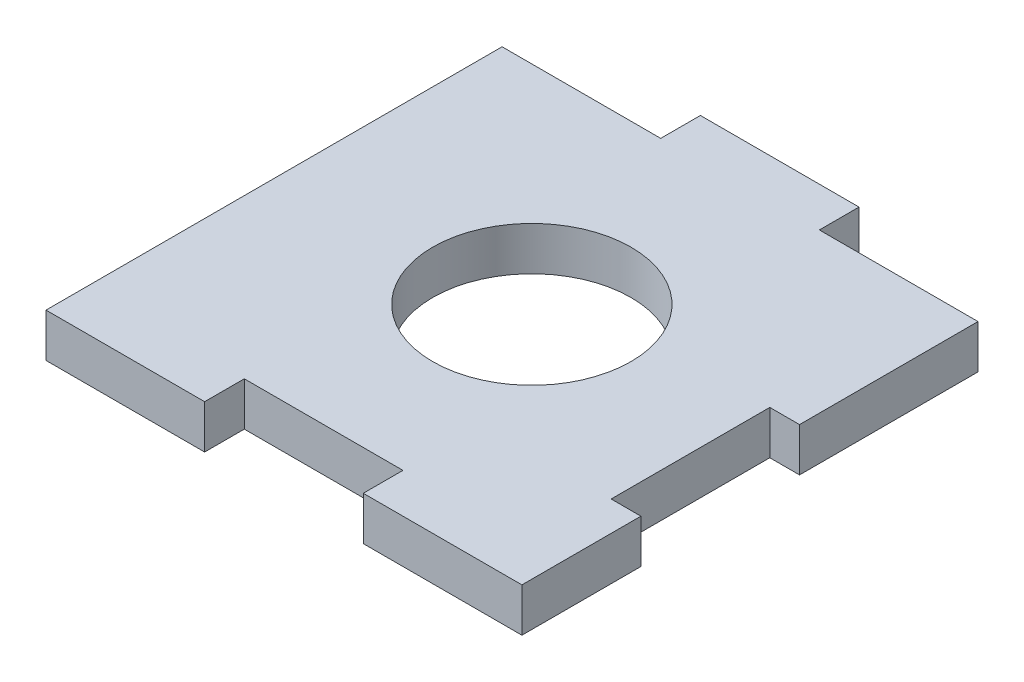
SolidWorks part; units mm, degrees
material "cardboard"
ref_plane "Front Plane" through (0, 0, 0) normal (0, 0, 1) x (1, 0, 0)
ref_plane "Top Plane" through (0, 0, 0) normal (0, 1, 0) x (1, 0, 0)
ref_plane "Right Plane" through (0, 0, 0) normal (1, 0, 0) x (0, 0, -1)
sketch "Sketch1" plane through (0, 0, 0) normal (0, 1, 0) x (1, 0, 0)
  line L0 (78.5546, 12.4023) -> (71.7044, 8.4474)
  line L1 (104.0546, -11.5977) -> (110.9047, -7.6428)
  line L2 (119.2044, 8.4474) -> (110.9047, 8.4474)
  line L3 (119.2044, -7.6428) -> (110.9047, -7.6428)
  line L4 (71.7044, 8.4474) -> (63.4047, 8.4474)
  line L5 (126.0546, 12.4023) -> (119.2044, 8.4474)
  line L6 (126.0546, -11.5977) -> (119.2044, -7.6428)
  line L7 (104.0546, 12.4023) -> (110.9047, 8.4474)
  line L8 (126.0546, 12.4023) -> (138.8046, 12.4023)
  line L9 (126.0546, -11.5977) -> (162.8046, -11.5977)
  line L10 (56.5546, 12.4023) -> (63.4047, 8.4474)
  line L11 (56.5546, -11.5977) -> (63.4047, -7.6428)
  line L12 (78.5546, -11.5977) -> (71.7044, -7.6428)
  line L13 (71.7044, -7.6428) -> (63.4047, -7.6428)
  line L14 (78.5546, 12.4023) -> (104.0546, 12.4023)
  line L15 (78.5546, -11.5977) -> (104.0546, -11.5977)
  line L16 (-11.1954, 78.1523) -> (-7.2405, 71.3021)
  line L17 (12.8046, 103.6523) -> (8.8496, 110.5024)
  line L18 (-7.2405, 118.8021) -> (-7.2405, 110.5024)
  line L19 (8.8496, 118.8021) -> (8.8496, 110.5024)
  line L20 (-7.2405, 71.3021) -> (-7.2405, 63.0024)
  line L21 (-11.1954, 125.6523) -> (-7.2405, 118.8021)
  line L22 (12.8046, 125.6523) -> (8.8496, 118.8021)
  line L23 (-11.1954, 103.6523) -> (-7.2405, 110.5024)
  line L24 (-11.1954, 125.6523) -> (-11.1954, 138.4023)
  line L25 (12.8046, 125.6523) -> (12.8046, 162.4023)
  line L26 (-11.1954, 56.1523) -> (-7.2405, 63.0024)
  line L27 (12.8046, 56.1523) -> (8.8496, 63.0024)
  line L28 (12.8046, 78.1523) -> (8.8496, 71.3021)
  line L29 (8.8496, 71.3021) -> (8.8496, 63.0024)
  line L30 (-11.1954, 78.1523) -> (-11.1954, 103.6523)
  line L31 (12.8046, 78.1523) -> (12.8046, 103.6523)
  line L32 (91.3046, 37.4023) -> (91.3046, 17.4023)
  line L33 (90.3046, 37.4023) -> (90.3046, 31.4023)
  line L34 (37.8046, 12.4023) -> (43.8046, 12.4023)
  line L35 (90.3046, 31.4023) -> (92.3046, 31.4023)
  line L36 (42.5546, 12.4023) -> (42.5546, 10.4023)
  line L37 (43.8046, 12.4023) -> (56.5546, 12.4023)
  line L38 (138.8046, 12.4023) -> (138.8046, -11.5977)
  line L39 (138.8046, 12.4023) -> (162.8046, 12.4023)
  line L40 (162.8046, 12.4023) -> (162.8046, 10.4023)
  line L41 (-27.6918, 14.7566) -> (0.8046, -13.7398)
  line L42 (-27.6918, 14.7566) -> (-13.5497, 28.8987)
  line L43 (0.8046, -13.7398) -> (14.9467, 0.4023)
  line L44 (-13.5497, 28.8987) -> (14.9467, 0.4023)
  line L45 (138.8046, 12.4023) -> (138.8046, 37.4023)
  line L46 (40.8046, 37.4023) -> (162.8046, 37.4023)
  line L47 (162.8046, 37.4023) -> (162.8046, 12.4023)
  line L48 (92.3046, 31.4023) -> (92.3046, 23.4023)
  line L49 (138.8046, 37.4023) -> (138.8046, 61.4023)
  line L50 (138.8046, 61.4023) -> (147.8046, 61.4023)
  line L51 (43.8046, 37.4023) -> (43.8046, 17.4023)
  line L52 (162.8046, 61.4023) -> (162.8046, 51.7243)
  line L53 (147.8046, 61.4023) -> (147.8046, 63.6023)
  line L54 (153.8046, 63.6023) -> (153.8046, 61.4023)
  line L55 (153.8046, 61.4023) -> (162.8046, 61.4023)
  line L56 (-58.1954, 138.4023) -> (-58.1954, 113.9023)
  line L57 (-38.1954, 113.9023) -> (-38.1954, 138.4023)
  line L58 (92.3046, 23.4023) -> (90.3046, 23.4023)
  line L59 (138.8046, -11.5977) -> (138.8046, -36.5977)
  line L60 (147.8046, -36.5977) -> (153.8046, -36.5977)
  line L61 (162.8046, -36.5977) -> (162.8046, -11.5977)
  line L62 (43.8046, -36.5977) -> (43.8046, -16.5977)
  line L63 (138.8046, -36.5977) -> (138.8046, -37.7777)
  line L64 (153.8046, -37.7777) -> (162.8046, -37.7777)
  line L65 (162.8046, -37.7777) -> (162.8046, -36.5977)
  line L66 (147.8046, -37.7777) -> (147.8046, -36.5977)
  line L67 (153.8046, -37.7777) -> (153.8046, -36.5977)
  line L68 (-37.3754, -137.5977) -> (-37.3754, -146.5977)
  line L69 (90.3046, 23.4023) -> (90.3046, 17.4023)
  line L70 (90.3046, 12.4023) -> (90.3046, 4.4023)
  line L71 (43.8046, -11.5977) -> (56.5546, -11.5977)
  line L72 (37.8046, -11.5977) -> (43.8046, -11.5977)
  line L73 (91.2784, 12.4023) -> (91.2784, -11.5977)
  line L74 (90.3046, 4.4023) -> (92.3046, 4.4023)
  line L75 (92.3046, 4.4023) -> (92.3046, -3.5977)
  line L76 (92.3046, -3.5977) -> (90.3046, -3.5977)
  line L77 (136.8046, 12.4023) -> (136.8046, 4.4023)
  line L78 (136.8046, 4.4023) -> (140.8046, 4.4023)
  line L79 (38.9846, 162.4023) -> (38.9846, 153.4023)
  line L80 (38.8046, 35.4023) -> (38.8046, 19.4023)
  line L81 (40.8046, 17.4023) -> (138.8046, 17.4023)
  line L82 (42.5546, 24.4023) -> (42.5546, 17.4023)
  line L83 (43.8046, 30.4023) -> (40.8046, 30.4023)
  line L84 (40.8046, 30.4023) -> (40.8046, 24.4023)
  line L85 (45.0546, 6.4023) -> (42.5546, 6.4023)
  line L86 (6.8046, -41.3477) -> (6.8046, -39.3477)
  line L87 (42.5546, -5.5977) -> (45.0546, -5.5977)
  line L88 (45.0546, 6.4023) -> (45.0546, -5.5977)
  line L89 (43.8046, 12.4023) -> (43.8046, 6.4023)
  line L90 (42.5546, 10.4023) -> (45.0546, 10.4023)
  line L91 (45.0546, 10.4023) -> (45.0546, 8.4023)
  line L92 (45.0546, 8.4023) -> (42.5546, 8.4023)
  line L93 (42.5546, 8.4023) -> (42.5546, 6.4023)
  line L94 (42.5546, -7.5977) -> (42.5546, -5.5977)
  line L95 (45.0546, -7.5977) -> (42.5546, -7.5977)
  line L96 (45.0546, -9.5977) -> (45.0546, -7.5977)
  line L97 (42.5546, -9.5977) -> (45.0546, -9.5977)
  line L98 (42.5546, -11.5977) -> (42.5546, -9.5977)
  line L99 (140.8046, 4.4023) -> (140.8046, -3.5977)
  line L100 (140.8046, -3.5977) -> (136.8046, -3.5977)
  line L101 (136.8046, -3.5977) -> (136.8046, -11.5977)
  line L102 (138.8046, 14.4023) -> (146.8046, 14.4023)
  line L103 (146.8046, 14.4023) -> (146.8046, 10.4023)
  line L104 (146.8046, 10.4023) -> (154.8046, 10.4023)
  line L105 (154.8046, 10.4023) -> (154.8046, 14.4023)
  line L106 (154.8046, 14.4023) -> (162.8046, 14.4023)
  line L107 (137.3046, 37.4023) -> (137.3046, 31.4023)
  line L108 (137.3046, 31.4023) -> (140.3046, 31.4023)
  line L109 (140.3046, 31.4023) -> (140.3046, 23.4023)
  line L110 (140.3046, 23.4023) -> (137.3046, 23.4023)
  line L111 (137.3046, 23.4023) -> (137.3046, 17.4023)
  line L112 (90.3046, -3.5977) -> (90.3046, -11.5977)
  line L113 (90.3046, -22.5977) -> (90.3046, -16.5977)
  line L114 (91.3046, -36.5977) -> (91.3046, -16.5977)
  line L115 (92.3046, -22.5977) -> (90.3046, -22.5977)
  line L116 (92.3046, -30.5977) -> (92.3046, -22.5977)
  line L117 (154.8046, -13.5977) -> (162.8046, -13.5977)
  line L118 (154.8046, -9.5977) -> (154.8046, -13.5977)
  line L119 (146.8046, -9.5977) -> (154.8046, -9.5977)
  line L120 (146.8046, -13.5977) -> (146.8046, -9.5977)
  line L121 (138.8046, -13.5977) -> (146.8046, -13.5977)
  line L122 (137.3046, -22.5977) -> (137.3046, -16.5977)
  line L123 (140.3046, -22.5977) -> (137.3046, -22.5977)
  line L124 (42.5546, 37.4023) -> (42.5546, 30.4023)
  line L125 (43.8046, 24.4023) -> (40.8046, 24.4023)
  line L126 (138.8046, -36.5977) -> (40.8046, -36.5977)
  line L127 (38.8046, -34.5977) -> (38.8046, -18.5977)
  line L128 (40.8046, -16.5977) -> (138.8046, -16.5977)
  line L129 (140.3046, -30.5977) -> (140.3046, -22.5977)
  line L130 (137.3046, -30.5977) -> (140.3046, -30.5977)
  line L131 (137.3046, -36.5977) -> (137.3046, -30.5977)
  line L132 (90.3046, -30.5977) -> (92.3046, -30.5977)
  line L133 (90.3046, -36.5977) -> (90.3046, -30.5977)
  line L134 (138.8046, 39.4023) -> (146.8046, 39.4023)
  line L135 (146.8046, 39.4023) -> (146.8046, 35.4023)
  line L136 (146.8046, 35.4023) -> (154.8046, 35.4023)
  line L137 (154.8046, 35.4023) -> (154.8046, 39.4023)
  line L138 (154.8046, 39.4023) -> (162.8046, 39.4023)
  line L139 (-43.6954, 134.1523) -> (-43.6954, 118.1523)
  line L140 (-55.1954, 134.1523) -> (-52.6954, 134.1523)
  line L141 (-55.1954, 134.1523) -> (-55.1954, 118.1523)
  line L142 (-55.1954, 118.1523) -> (-52.6954, 118.1523)
  line L143 (-52.6954, 134.1523) -> (-52.6954, 118.1523)
  line L144 (42.5546, -23.5977) -> (42.5546, -16.5977)
  line L145 (43.8046, -23.5977) -> (40.8046, -23.5977)
  line L146 (40.8046, -29.5977) -> (40.8046, -23.5977)
  line L147 (43.8046, -29.5977) -> (40.8046, -29.5977)
  line L148 (42.5546, -36.5977) -> (42.5546, -29.5977)
  line L149 (197.8046, 5.4023) -> (197.8046, -4.5977)
  line L150 (192.8046, 10.4023) -> (162.8046, 10.4023)
  line L151 (192.8046, -9.5977) -> (162.8046, -9.5977)
  line L152 (192.8046, 10.4023) -> (197.8046, 5.4023)
  line L153 (197.8046, -4.5977) -> (192.8046, -9.5977)
  line L154 (162.8046, -9.5977) -> (162.8046, -11.5977)
  line L155 (138.8046, 63.6023) -> (147.8046, 63.6023)
  line L156 (138.8046, 63.6023) -> (138.8046, 65.6023)
  line L157 (138.8046, 65.6023) -> (162.8046, 65.6023)
  line L158 (162.8046, 65.6023) -> (162.8046, 63.6023)
  line L159 (153.8046, 63.6023) -> (162.8046, 63.6023)
  line L160 (-41.1954, 118.1523) -> (-43.6954, 118.1523)
  line L161 (-41.1954, 134.1523) -> (-41.1954, 118.1523)
  line L162 (-41.1954, 134.1523) -> (-43.6954, 134.1523)
  line L163 (156.2046, 51.7243) -> (162.8046, 51.7243)
  line L164 (156.2046, 51.7243) -> (156.2046, 47.2243)
  line L165 (156.2046, 47.2243) -> (162.8046, 47.2243)
  line L166 (162.8046, 47.2243) -> (162.8046, 37.4023)
  line L167 (12.8046, -77.3477) -> (8.8496, -70.4976)
  line L168 (-11.1954, -102.8477) -> (-7.2405, -109.6979)
  line L169 (8.8496, -117.9976) -> (8.8496, -109.6979)
  line L170 (12.8046, -36.5977) -> (12.8046, -42.5977)
  line L171 (12.8046, -41.3477) -> (10.8046, -41.3477)
  line L172 (12.8046, -42.5977) -> (12.8046, -55.3477)
  line L173 (-7.2405, -117.9976) -> (-7.2405, -109.6979)
  line L174 (8.8496, -70.4976) -> (8.8496, -62.1979)
  line L175 (12.8046, -124.8477) -> (8.8496, -117.9976)
  line L176 (-11.1954, -124.8477) -> (-7.2405, -117.9976)
  line L177 (12.8046, -102.8477) -> (8.8496, -109.6979)
  line L178 (12.8046, -124.8477) -> (12.8046, -137.5977)
  line L179 (-11.1954, -124.8477) -> (-11.1954, -161.5977)
  line L180 (12.8046, -55.3477) -> (8.8496, -62.1979)
  line L181 (-11.1954, -55.3477) -> (-7.2405, -62.1979)
  line L182 (37.8046, -42.5977) -> (17.8046, -42.5977)
  line L183 (-11.1954, -77.3477) -> (-7.2405, -70.4976)
  line L184 (-7.2405, -70.4976) -> (-7.2405, -62.1979)
  line L185 (12.8046, -77.3477) -> (12.8046, -102.8477)
  line L186 (-11.1954, -77.3477) -> (-11.1954, -102.8477)
  line L187 (37.8046, -90.0977) -> (17.8046, -90.0977)
  line L188 (37.8046, -89.0977) -> (31.8046, -89.0977)
  line L189 (31.8046, -89.0977) -> (31.8046, -91.0977)
  line L190 (12.8046, -137.5977) -> (-11.1954, -137.5977)
  line L191 (12.8046, -137.5977) -> (12.8046, -161.5977)
  line L192 (12.8046, -161.5977) -> (10.8046, -161.5977)
  line L193 (12.8046, -137.5977) -> (37.8046, -137.5977)
  line L194 (37.8046, -39.5977) -> (37.8046, -161.5977)
  line L195 (-36.1954, -42.5977) -> (-16.1954, -42.5977)
  line L196 (37.8046, -161.5977) -> (12.8046, -161.5977)
  line L197 (31.8046, -91.0977) -> (23.8046, -91.0977)
  line L198 (37.8046, -137.5977) -> (61.8046, -137.5977)
  line L199 (61.8046, -137.5977) -> (61.8046, -146.5977)
  line L200 (61.8046, -161.5977) -> (52.1265, -161.5977)
  line L201 (61.8046, -146.5977) -> (64.0046, -146.5977)
  line L202 (64.0046, -152.5977) -> (61.8046, -152.5977)
  line L203 (61.8046, -152.5977) -> (61.8046, -161.5977)
  line L204 (-11.1954, -42.5977) -> (-11.1954, -55.3477)
  line L205 (-11.1954, -36.5977) -> (-11.1954, -42.5977)
  line L206 (23.8046, -91.0977) -> (23.8046, -89.0977)
  line L207 (-11.1954, -137.5977) -> (-36.1954, -137.5977)
  line L208 (-36.1954, -146.5977) -> (-36.1954, -152.5977)
  line L209 (38.9846, 147.4023) -> (38.9846, 138.4023)
  line L210 (35.8046, -37.5977) -> (19.8046, -37.5977)
  line L211 (17.8046, -39.5977) -> (17.8046, -137.5977)
  line L212 (24.8046, -41.3477) -> (17.8046, -41.3477)
  line L213 (30.8046, -42.5977) -> (30.8046, -39.5977)
  line L214 (30.8046, -39.5977) -> (24.8046, -39.5977)
  line L215 (6.8046, -43.8477) -> (6.8046, -41.3477)
  line L216 (-36.1954, -161.5977) -> (-11.1954, -161.5977)
  line L217 (-5.1954, -41.3477) -> (-5.1954, -43.8477)
  line L218 (6.8046, -43.8477) -> (-5.1954, -43.8477)
  line L219 (12.8046, -42.5977) -> (6.8046, -42.5977)
  line L220 (10.8046, -41.3477) -> (10.8046, -43.8477)
  line L221 (10.8046, -43.8477) -> (8.8046, -43.8477)
  line L222 (8.8046, -43.8477) -> (8.8046, -41.3477)
  line L223 (8.8046, -41.3477) -> (6.8046, -41.3477)
  line L224 (-7.1954, -41.3477) -> (-5.1954, -41.3477)
  line L225 (-7.1954, -43.8477) -> (-7.1954, -41.3477)
  line L226 (-9.1954, -43.8477) -> (-7.1954, -43.8477)
  line L227 (-9.1954, -41.3477) -> (-9.1954, -43.8477)
  line L228 (-11.1954, -41.3477) -> (-9.1954, -41.3477)
  line L229 (-36.1954, -137.5977) -> (-37.3754, -137.5977)
  line L230 (-37.3754, -152.5977) -> (-37.3754, -161.5977)
  line L231 (-37.3754, -161.5977) -> (-36.1954, -161.5977)
  line L232 (-37.3754, -146.5977) -> (-36.1954, -146.5977)
  line L233 (-37.3754, -152.5977) -> (-36.1954, -152.5977)
  line L234 (-161.1954, 38.5823) -> (-152.1954, 38.5823)
  line L235 (23.8046, -89.0977) -> (17.8046, -89.0977)
  line L236 (12.8046, -89.0977) -> (4.8046, -89.0977)
  line L237 (12.8046, -90.0715) -> (-11.1954, -90.0715)
  line L238 (4.8046, -89.0977) -> (4.8046, -91.0977)
  line L239 (4.8046, -91.0977) -> (-3.1954, -91.0977)
  line L240 (-3.1954, -91.0977) -> (-3.1954, -89.0977)
  line L241 (12.8046, -135.5977) -> (4.8046, -135.5977)
  line L242 (4.8046, -135.5977) -> (4.8046, -139.5977)
  line L243 (4.8046, -139.5977) -> (-3.1954, -139.5977)
  line L244 (-3.1954, -139.5977) -> (-3.1954, -135.5977)
  line L245 (-3.1954, -135.5977) -> (-11.1954, -135.5977)
  line L246 (14.8046, -137.5977) -> (14.8046, -145.5977)
  line L247 (14.8046, -145.5977) -> (10.8046, -145.5977)
  line L248 (10.8046, -145.5977) -> (10.8046, -153.5977)
  line L249 (10.8046, -153.5977) -> (14.8046, -153.5977)
  line L250 (14.8046, -153.5977) -> (14.8046, -161.5977)
  line L251 (37.8046, -136.0977) -> (31.8046, -136.0977)
  line L252 (31.8046, -136.0977) -> (31.8046, -139.0977)
  line L253 (31.8046, -139.0977) -> (23.8046, -139.0977)
  line L254 (37.8046, -41.3477) -> (30.8046, -41.3477)
  line L255 (24.8046, -42.5977) -> (24.8046, -39.5977)
  line L256 (-36.1954, -137.5977) -> (-36.1954, -39.5977)
  line L257 (-34.1954, -37.5977) -> (-18.1954, -37.5977)
  line L258 (-16.1954, -39.5977) -> (-16.1954, -137.5977)
  line L259 (23.8046, -139.0977) -> (23.8046, -136.0977)
  line L260 (23.8046, -136.0977) -> (17.8046, -136.0977)
  line L261 (-3.1954, -89.0977) -> (-11.1954, -89.0977)
  line L262 (-22.1954, -89.0977) -> (-16.1954, -89.0977)
  line L263 (-36.1954, -90.0977) -> (-16.1954, -90.0977)
  line L264 (-22.1954, -91.0977) -> (-22.1954, -89.0977)
  line L265 (-30.1954, -91.0977) -> (-22.1954, -91.0977)
  line L266 (-13.1954, -153.5977) -> (-13.1954, -161.5977)
  line L267 (-9.1954, -153.5977) -> (-13.1954, -153.5977)
  line L268 (-9.1954, -145.5977) -> (-9.1954, -153.5977)
  line L269 (-13.1954, -145.5977) -> (-9.1954, -145.5977)
  line L270 (-13.1954, -137.5977) -> (-13.1954, -145.5977)
  line L271 (-22.1954, -136.0977) -> (-16.1954, -136.0977)
  line L272 (-22.1954, -139.0977) -> (-22.1954, -136.0977)
  line L273 (-30.1954, -139.0977) -> (-22.1954, -139.0977)
  line L274 (-23.1954, -41.3477) -> (-16.1954, -41.3477)
  line L275 (-23.1954, -42.5977) -> (-23.1954, -39.5977)
  line L276 (-29.1954, -39.5977) -> (-23.1954, -39.5977)
  line L277 (-29.1954, -42.5977) -> (-29.1954, -39.5977)
  line L278 (-36.1954, -41.3477) -> (-29.1954, -41.3477)
  line L279 (-30.1954, -136.0977) -> (-30.1954, -139.0977)
  line L280 (-36.1954, -136.0977) -> (-30.1954, -136.0977)
  line L281 (-30.1954, -89.0977) -> (-30.1954, -91.0977)
  line L282 (-36.1954, -89.0977) -> (-30.1954, -89.0977)
  line L283 (39.8046, -137.5977) -> (39.8046, -145.5977)
  line L284 (39.8046, -145.5977) -> (35.8046, -145.5977)
  line L285 (35.8046, -145.5977) -> (35.8046, -153.5977)
  line L286 (35.8046, -153.5977) -> (39.8046, -153.5977)
  line L287 (39.8046, -153.5977) -> (39.8046, -161.5977)
  line L288 (5.8046, -196.5977) -> (-4.1954, -196.5977)
  line L289 (10.8046, -191.5977) -> (10.8046, -161.5977)
  line L290 (-9.1954, -191.5977) -> (-9.1954, -161.5977)
  line L291 (10.8046, -191.5977) -> (5.8046, -196.5977)
  line L292 (-4.1954, -196.5977) -> (-9.1954, -191.5977)
  line L293 (-9.1954, -161.5977) -> (-11.1954, -161.5977)
  line L294 (64.0046, -137.5977) -> (64.0046, -146.5977)
  line L295 (64.0046, -137.5977) -> (66.0046, -137.5977)
  line L296 (66.0046, -137.5977) -> (66.0046, -161.5977)
  line L297 (66.0046, -161.5977) -> (64.0046, -161.5977)
  line L298 (64.0046, -152.5977) -> (64.0046, -161.5977)
  line L299 (-36.1954, -11.5977) -> (-42.1954, -11.5977)
  line L300 (-40.9454, -11.5977) -> (-40.9454, -9.5977)
  line L301 (-42.1954, -11.5977) -> (-54.9454, -11.5977)
  line L302 (52.1265, -154.9977) -> (52.1265, -161.5977)
  line L303 (52.1265, -154.9977) -> (47.6265, -154.9977)
  line L304 (-42.1954, -36.5977) -> (-42.1954, -16.5977)
  line L305 (47.6265, -154.9977) -> (47.6265, -161.5977)
  line L306 (47.6265, -161.5977) -> (37.8046, -161.5977)
  line L307 (-76.9454, -11.5977) -> (-70.0953, -7.6428)
  line L308 (-102.4454, 12.4023) -> (-109.2956, 8.4474)
  line L309 (-117.5953, -7.6428) -> (-109.2956, -7.6428)
  line L310 (-117.5953, 8.4474) -> (-109.2956, 8.4474)
  line L311 (-70.0953, -7.6428) -> (-61.7956, -7.6428)
  line L312 (-124.4454, -11.5977) -> (-117.5953, -7.6428)
  line L313 (-124.4454, 12.4023) -> (-117.5953, 8.4474)
  line L314 (-102.4454, -11.5977) -> (-109.2956, -7.6428)
  line L315 (-124.4454, -11.5977) -> (-137.1954, -11.5977)
  line L316 (-42.1954, 37.4023) -> (-42.1954, 17.4023)
  line L317 (-124.4454, 12.4023) -> (-161.1954, 12.4023)
  line L318 (-54.9454, -11.5977) -> (-61.7956, -7.6428)
  line L319 (-54.9454, 12.4023) -> (-61.7956, 8.4474)
  line L320 (-76.9454, 12.4023) -> (-70.0953, 8.4474)
  line L321 (-70.0953, 8.4474) -> (-61.7956, 8.4474)
  line L322 (-76.9454, -11.5977) -> (-102.4454, -11.5977)
  line L323 (-76.9454, 12.4023) -> (-102.4454, 12.4023)
  line L324 (-89.6954, -36.5977) -> (-89.6954, -16.5977)
  line L325 (-42.1954, 12.4023) -> (-54.9454, 12.4023)
  line L326 (-36.1954, 12.4023) -> (-42.1954, 12.4023)
  line L327 (-88.6954, -36.5977) -> (-88.6954, -30.5977)
  line L328 (-88.6954, -30.5977) -> (-90.6954, -30.5977)
  line L329 (-137.1954, -11.5977) -> (-137.1954, 12.4023)
  line L330 (-137.1954, -11.5977) -> (-161.1954, -11.5977)
  line L331 (-161.1954, -11.5977) -> (-161.1954, -9.5977)
  line L332 (-137.1954, -11.5977) -> (-137.1954, -36.5977)
  line L333 (138.8046, -37.7777) -> (147.8046, -37.7777)
  line L334 (-37.1954, -34.5977) -> (-37.1954, -18.5977)
  line L335 (-39.1954, -16.5977) -> (-137.1954, -16.5977)
  line L336 (-40.9454, -23.5977) -> (-40.9454, -16.5977)
  line L337 (-42.1954, -29.5977) -> (-39.1954, -29.5977)
  line L338 (-39.1954, -29.5977) -> (-39.1954, -23.5977)
  line L339 (-43.4454, -5.5977) -> (-40.9454, -5.5977)
  line L340 (-39.1954, -36.5977) -> (-161.1954, -36.5977)
  line L341 (-40.9454, 6.4023) -> (-43.4454, 6.4023)
  line L342 (-43.4454, -5.5977) -> (-43.4454, 6.4023)
  line L343 (-42.1954, -11.5977) -> (-42.1954, -5.5977)
  line L344 (-40.9454, -9.5977) -> (-43.4454, -9.5977)
  line L345 (-43.4454, -9.5977) -> (-43.4454, -7.5977)
  line L346 (-43.4454, -7.5977) -> (-40.9454, -7.5977)
  line L347 (-40.9454, -7.5977) -> (-40.9454, -5.5977)
  line L348 (-40.9454, 8.4023) -> (-40.9454, 6.4023)
  line L349 (-43.4454, 8.4023) -> (-40.9454, 8.4023)
  line L350 (-43.4454, 10.4023) -> (-43.4454, 8.4023)
  line L351 (-40.9454, 10.4023) -> (-43.4454, 10.4023)
  line L352 (-40.9454, 12.4023) -> (-40.9454, 10.4023)
  line L353 (-161.1954, -36.5977) -> (-161.1954, -11.5977)
  line L354 (-90.6954, -30.5977) -> (-90.6954, -22.5977)
  line L355 (-137.1954, -36.5977) -> (-137.1954, -60.5977)
  line L356 (-137.1954, -60.5977) -> (-146.1954, -60.5977)
  line L357 (-161.1954, -60.5977) -> (-161.1954, -50.9197)
  line L358 (-146.1954, -60.5977) -> (-146.1954, -62.7977)
  line L359 (-152.1954, -62.7977) -> (-152.1954, -60.5977)
  line L360 (-152.1954, -60.5977) -> (-161.1954, -60.5977)
  line L361 (-90.6954, -22.5977) -> (-88.6954, -22.5977)
  line L362 (-137.1954, 12.4023) -> (-137.1954, 37.4023)
  line L363 (-146.1954, 37.4023) -> (-152.1954, 37.4023)
  line L364 (-161.1954, 37.4023) -> (-161.1954, 12.4023)
  line L365 (-137.1954, 37.4023) -> (-137.1954, 38.5823)
  line L366 (-161.1954, 38.5823) -> (-161.1954, 37.4023)
  line L367 (-146.1954, 38.5823) -> (-146.1954, 37.4023)
  line L368 (-152.1954, 38.5823) -> (-152.1954, 37.4023)
  line L369 (-146.1954, 38.5823) -> (-137.1954, 38.5823)
  line L370 (-88.6954, -22.5977) -> (-88.6954, -16.5977)
  line L371 (-88.6954, -11.5977) -> (-88.6954, -3.5977)
  line L372 (-89.6692, -11.5977) -> (-89.6692, 12.4023)
  line L373 (-88.6954, -3.5977) -> (-90.6954, -3.5977)
  line L374 (-40.9454, -36.5977) -> (-40.9454, -29.5977)
  line L375 (-42.1954, -23.5977) -> (-39.1954, -23.5977)
  line L376 (-137.1954, 37.4023) -> (-39.1954, 37.4023)
  line L377 (-37.1954, 35.4023) -> (-37.1954, 19.4023)
  line L378 (-39.1954, 17.4023) -> (-137.1954, 17.4023)
  line L379 (-90.6954, -3.5977) -> (-90.6954, 4.4023)
  line L380 (-90.6954, 4.4023) -> (-88.6954, 4.4023)
  line L381 (-135.1954, -11.5977) -> (-135.1954, -3.5977)
  line L382 (-135.1954, -3.5977) -> (-139.1954, -3.5977)
  line L383 (-139.1954, -3.5977) -> (-139.1954, 4.4023)
  line L384 (-139.1954, 4.4023) -> (-135.1954, 4.4023)
  line L385 (-135.1954, 4.4023) -> (-135.1954, 12.4023)
  line L386 (-137.1954, -13.5977) -> (-145.1954, -13.5977)
  line L387 (-145.1954, -13.5977) -> (-145.1954, -9.5977)
  line L388 (-145.1954, -9.5977) -> (-153.1954, -9.5977)
  line L389 (-153.1954, -9.5977) -> (-153.1954, -13.5977)
  line L390 (-153.1954, -13.5977) -> (-161.1954, -13.5977)
  line L391 (-135.6954, -36.5977) -> (-135.6954, -30.5977)
  line L392 (-36.1954, 90.9023) -> (-16.1954, 90.9023)
  line L393 (-36.1954, 89.9023) -> (-30.1954, 89.9023)
  line L394 (-40.9454, 24.4023) -> (-40.9454, 17.4023)
  line L395 (-42.1954, 24.4023) -> (-39.1954, 24.4023)
  line L396 (-39.1954, 30.4023) -> (-39.1954, 24.4023)
  line L397 (-42.1954, 30.4023) -> (-39.1954, 30.4023)
  line L398 (-40.9454, 37.4023) -> (-40.9454, 30.4023)
  line L399 (-135.6954, -30.5977) -> (-138.6954, -30.5977)
  line L400 (-138.6954, -30.5977) -> (-138.6954, -22.5977)
  line L401 (-138.6954, -22.5977) -> (-135.6954, -22.5977)
  line L402 (-135.6954, -22.5977) -> (-135.6954, -16.5977)
  line L403 (-88.6954, 4.4023) -> (-88.6954, 12.4023)
  line L404 (-88.6954, 23.4023) -> (-88.6954, 17.4023)
  line L405 (-89.6954, 37.4023) -> (-89.6954, 17.4023)
  line L406 (-90.6954, 23.4023) -> (-88.6954, 23.4023)
  line L407 (-90.6954, 31.4023) -> (-90.6954, 23.4023)
  line L408 (-153.1954, 14.4023) -> (-161.1954, 14.4023)
  line L409 (-153.1954, 10.4023) -> (-153.1954, 14.4023)
  line L410 (-145.1954, 10.4023) -> (-153.1954, 10.4023)
  line L411 (-145.1954, 14.4023) -> (-145.1954, 10.4023)
  line L412 (-137.1954, 14.4023) -> (-145.1954, 14.4023)
  line L413 (-135.6954, 23.4023) -> (-135.6954, 17.4023)
  line L414 (-138.6954, 23.4023) -> (-135.6954, 23.4023)
  line L415 (-138.6954, 31.4023) -> (-138.6954, 23.4023)
  line L416 (-135.6954, 31.4023) -> (-138.6954, 31.4023)
  line L417 (-135.6954, 37.4023) -> (-135.6954, 31.4023)
  line L418 (-88.6954, 31.4023) -> (-90.6954, 31.4023)
  line L419 (-88.6954, 37.4023) -> (-88.6954, 31.4023)
  line L420 (-137.1954, -38.5977) -> (-145.1954, -38.5977)
  line L421 (-145.1954, -38.5977) -> (-145.1954, -34.5977)
  line L422 (-145.1954, -34.5977) -> (-153.1954, -34.5977)
  line L423 (-153.1954, -34.5977) -> (-153.1954, -38.5977)
  line L424 (-153.1954, -38.5977) -> (-161.1954, -38.5977)
  line L425 (-11.1954, 42.1523) -> (-9.1954, 42.1523)
  line L426 (-30.1954, 89.9023) -> (-30.1954, 91.9023)
  line L427 (-11.1954, 138.4023) -> (12.8046, 138.4023)
  line L428 (-11.1954, 138.4023) -> (-11.1954, 162.4023)
  line L429 (-11.1954, 162.4023) -> (-9.1954, 162.4023)
  line L430 (-11.1954, 138.4023) -> (-36.1954, 138.4023)
  line L431 (-36.1954, 138.4023) -> (-36.1954, 162.4023)
  line L432 (-36.1954, 162.4023) -> (-11.1954, 162.4023)
  line L433 (-36.1954, 138.4023) -> (-36.1954, 43.4023)
  line L434 (-36.1954, 43.4023) -> (-16.1954, 43.4023)
  line L435 (-16.1954, 43.4023) -> (-16.1954, 138.4023)
  line L436 (-30.1954, 91.9023) -> (-22.1954, 91.9023)
  line L437 (-36.1954, 138.4023) -> (-60.1954, 138.4023)
  line L438 (-60.1954, 138.4023) -> (-60.1954, 147.4023)
  line L439 (-60.1954, 162.4023) -> (-50.5174, 162.4023)
  line L440 (-60.1954, 147.4023) -> (-62.3954, 147.4023)
  line L441 (-62.3954, 153.4023) -> (-60.1954, 153.4023)
  line L442 (-60.1954, 153.4023) -> (-60.1954, 162.4023)
  line L443 (-58.1954, 113.9023) -> (-38.1954, 113.9023)
  line L444 (37.8046, 43.4023) -> (17.8046, 43.4023)
  line L445 (-22.1954, 91.9023) -> (-22.1954, 89.9023)
  line L446 (37.8046, 138.4023) -> (37.8046, 43.4023)
  line L447 (17.8046, 43.4023) -> (17.8046, 138.4023)
  line L448 (12.8046, 138.4023) -> (37.8046, 138.4023)
  line L449 (37.8046, 147.4023) -> (37.8046, 153.4023)
  line L450 (37.8046, 162.4023) -> (12.8046, 162.4023)
  line L451 (12.8046, 37.4023) -> (12.8046, 56.1523)
  line L452 (37.8046, 138.4023) -> (38.9846, 138.4023)
  line L453 (38.9846, 162.4023) -> (37.8046, 162.4023)
  line L454 (38.9846, 147.4023) -> (37.8046, 147.4023)
  line L455 (38.9846, 153.4023) -> (37.8046, 153.4023)
  line L456 (-36.1954, 43.4023) -> (-36.1954, 40.4023)
  line L457 (-34.1954, 38.4023) -> (-18.1954, 38.4023)
  line L458 (-16.1954, 40.4023) -> (-16.1954, 43.4023)
  line L459 (35.8046, 38.4023) -> (19.8046, 38.4023)
  line L460 (17.8046, 40.4023) -> (17.8046, 43.4023)
  line L461 (-5.1954, 44.6523) -> (-5.1954, 42.1523)
  line L462 (-22.1954, 89.9023) -> (-16.1954, 89.9023)
  line L463 (6.8046, 42.1523) -> (6.8046, 44.6523)
  line L464 (-5.1954, 44.6523) -> (6.8046, 44.6523)
  line L465 (-11.1954, 43.4023) -> (-5.1954, 43.4023)
  line L466 (-9.1954, 42.1523) -> (-9.1954, 44.6523)
  line L467 (-9.1954, 44.6523) -> (-7.1954, 44.6523)
  line L468 (-7.1954, 44.6523) -> (-7.1954, 42.1523)
  line L469 (-7.1954, 42.1523) -> (-5.1954, 42.1523)
  line L470 (8.8046, 42.1523) -> (6.8046, 42.1523)
  line L471 (8.8046, 44.6523) -> (8.8046, 42.1523)
  line L472 (10.8046, 44.6523) -> (8.8046, 44.6523)
  line L473 (10.8046, 42.1523) -> (10.8046, 44.6523)
  line L474 (12.8046, 42.1523) -> (10.8046, 42.1523)
  line L475 (-11.1954, 89.9023) -> (-3.1954, 89.9023)
  line L476 (-11.1954, 90.8761) -> (12.8046, 90.8761)
  line L477 (-3.1954, 89.9023) -> (-3.1954, 91.9023)
  line L478 (-3.1954, 91.9023) -> (4.8046, 91.9023)
  line L479 (4.8046, 91.9023) -> (4.8046, 89.9023)
  line L480 (-11.1954, 136.4023) -> (-3.1954, 136.4023)
  line L481 (-3.1954, 136.4023) -> (-3.1954, 140.4023)
  line L482 (-3.1954, 140.4023) -> (4.8046, 140.4023)
  line L483 (4.8046, 140.4023) -> (4.8046, 136.4023)
  line L484 (4.8046, 136.4023) -> (12.8046, 136.4023)
  line L485 (-13.1954, 138.4023) -> (-13.1954, 146.4023)
  line L486 (-13.1954, 146.4023) -> (-9.1954, 146.4023)
  line L487 (-9.1954, 146.4023) -> (-9.1954, 154.4023)
  line L488 (-9.1954, 154.4023) -> (-13.1954, 154.4023)
  line L489 (-13.1954, 154.4023) -> (-13.1954, 162.4023)
  line L490 (-36.1954, 136.9023) -> (-30.1954, 136.9023)
  line L491 (-30.1954, 136.9023) -> (-30.1954, 139.9023)
  line L492 (-30.1954, 139.9023) -> (-22.1954, 139.9023)
  line L493 (-22.1954, 139.9023) -> (-22.1954, 136.9023)
  line L494 (-22.1954, 136.9023) -> (-16.1954, 136.9023)
  line L495 (4.8046, 89.9023) -> (12.8046, 89.9023)
  line L496 (23.8046, 89.9023) -> (17.8046, 89.9023)
  line L497 (37.8046, 90.9023) -> (17.8046, 90.9023)
  line L498 (23.8046, 91.9023) -> (23.8046, 89.9023)
  line L499 (31.8046, 91.9023) -> (23.8046, 91.9023)
  line L500 (-36.1954, 42.1523) -> (-29.1954, 42.1523)
  line L501 (30.8046, 40.4023) -> (24.8046, 40.4023)
  line L502 (24.8046, 42.1523) -> (17.8046, 42.1523)
  line L503 (-29.1954, 43.4023) -> (-29.1954, 40.4023)
  line L504 (-23.1954, 42.1523) -> (-16.1954, 42.1523)
  line L505 (14.8046, 154.4023) -> (14.8046, 162.4023)
  line L506 (10.8046, 154.4023) -> (14.8046, 154.4023)
  line L507 (10.8046, 146.4023) -> (10.8046, 154.4023)
  line L508 (14.8046, 146.4023) -> (10.8046, 146.4023)
  line L509 (14.8046, 138.4023) -> (14.8046, 146.4023)
  line L510 (23.8046, 136.9023) -> (17.8046, 136.9023)
  line L511 (23.8046, 139.9023) -> (23.8046, 136.9023)
  line L512 (31.8046, 139.9023) -> (23.8046, 139.9023)
  line L513 (31.8046, 136.9023) -> (31.8046, 139.9023)
  line L514 (37.8046, 136.9023) -> (31.8046, 136.9023)
  line L515 (31.8046, 89.9023) -> (31.8046, 91.9023)
  line L516 (37.8046, 89.9023) -> (31.8046, 89.9023)
  line L517 (12.8046, 37.4023) -> (21.769, 28.4378)
  line L518 (37.8046, -11.5977) -> (28.8401, -20.5622)
  line L519 (-11.1954, -36.5977) -> (-20.1599, -27.6332)
  line L520 (24.8046, 43.4023) -> (24.8046, 40.4023)
  line L521 (-23.1954, 43.4023) -> (-23.1954, 40.4023)
  line L522 (30.8046, 43.4023) -> (30.8046, 40.4023)
  line L523 (37.8046, 42.1523) -> (30.8046, 42.1523)
  line L524 (-38.1954, 138.4023) -> (-38.1954, 146.4023)
  line L525 (-38.1954, 146.4023) -> (-34.1954, 146.4023)
  line L526 (-34.1954, 146.4023) -> (-34.1954, 154.4023)
  line L527 (-34.1954, 154.4023) -> (-38.1954, 154.4023)
  line L528 (-38.1954, 154.4023) -> (-38.1954, 162.4023)
  line L529 (-58.1954, 136.9023) -> (-51.1954, 136.9023)
  line L530 (-51.1954, 136.9023) -> (-51.1954, 139.9023)
  line L531 (-51.1954, 139.9023) -> (-45.1954, 139.9023)
  line L532 (-45.1954, 139.9023) -> (-45.1954, 136.9023)
  line L533 (-45.1954, 136.9023) -> (-38.1954, 136.9023)
  line L534 (-11.1954, 37.4023) -> (-11.1954, 56.1523)
  line L535 (43.8046, -5.5977) -> (43.8046, -11.5977)
  line L536 (6.8046, 43.4023) -> (12.8046, 43.4023)
  line L537 (-42.1954, 6.4023) -> (-42.1954, 12.4023)
  line L538 (-5.1954, -42.5977) -> (-11.1954, -42.5977)
  line L539 (-4.1954, 197.4023) -> (5.8046, 197.4023)
  line L540 (-9.1954, 192.4023) -> (-9.1954, 162.4023)
  line L541 (10.8046, 192.4023) -> (10.8046, 162.4023)
  line L542 (-9.1954, 192.4023) -> (-4.1954, 197.4023)
  line L543 (5.8046, 197.4023) -> (10.8046, 192.4023)
  line L544 (134.5546, 56.4023) -> (118.5546, 56.4023)
  line L545 (134.5546, 56.4023) -> (134.5546, 53.9023)
  line L546 (-196.1954, -4.5977) -> (-196.1954, 5.4023)
  line L547 (-191.1954, -9.5977) -> (-161.1954, -9.5977)
  line L548 (-191.1954, 10.4023) -> (-161.1954, 10.4023)
  line L549 (-191.1954, -9.5977) -> (-196.1954, -4.5977)
  line L550 (-196.1954, 5.4023) -> (-191.1954, 10.4023)
  line L551 (-161.1954, 10.4023) -> (-161.1954, 12.4023)
  line L552 (-137.1954, -62.7977) -> (-146.1954, -62.7977)
  line L553 (-137.1954, -62.7977) -> (-137.1954, -64.7977)
  line L554 (-137.1954, -64.7977) -> (-161.1954, -64.7977)
  line L555 (-161.1954, -64.7977) -> (-161.1954, -62.7977)
  line L556 (10.8046, 162.4023) -> (12.8046, 162.4023)
  line L557 (-152.1954, -62.7977) -> (-161.1954, -62.7977)
  line L558 (134.5546, 53.9023) -> (118.5546, 53.9023)
  line L559 (118.5546, 56.4023) -> (118.5546, 53.9023)
  line L560 (134.5546, 44.9023) -> (118.5546, 44.9023)
  line L561 (134.5546, 42.4023) -> (134.5546, 44.9023)
  line L562 (134.5546, 42.4023) -> (118.5546, 42.4023)
  line L563 (118.5546, 42.4023) -> (118.5546, 44.9023)
  line L564 (137.3046, 59.4023) -> (137.3046, 52.4023)
  line L565 (137.3046, 52.4023) -> (140.3046, 52.4023)
  line L566 (-154.5954, -50.9197) -> (-161.1954, -50.9197)
  line L567 (-154.5954, -50.9197) -> (-154.5954, -46.4197)
  line L568 (-154.5954, -46.4197) -> (-161.1954, -46.4197)
  line L569 (-62.3954, 138.4023) -> (-62.3954, 147.4023)
  line L570 (-62.3954, 138.4023) -> (-64.3954, 138.4023)
  line L571 (-64.3954, 138.4023) -> (-64.3954, 162.4023)
  line L572 (-64.3954, 162.4023) -> (-62.3954, 162.4023)
  line L573 (-62.3954, 153.4023) -> (-62.3954, 162.4023)
  line L574 (-161.1954, -46.4197) -> (-161.1954, -36.5977)
  line L575 (140.3046, 52.4023) -> (140.3046, 46.4023)
  line L576 (-45.5575, 124.2471) -> (-46.6954, 124.2471)
  line L577 (-50.8334, 128.2884) -> (-49.6954, 128.2884)
  line L578 (-50.8334, 128.2884) -> (-50.8334, 124.2471)
  line L579 (-50.8334, 124.2471) -> (-49.6954, 124.2471)
  line L580 (-49.6954, 128.2884) -> (-49.6954, 124.2471)
  line L581 (-46.6954, 128.2884) -> (-46.6954, 124.2471)
  line L582 (-45.5575, 128.2884) -> (-46.6954, 128.2884)
  line L583 (-45.5575, 128.2884) -> (-45.5575, 124.2471)
  line L584 (140.3046, 46.4023) -> (137.3046, 46.4023)
  line L585 (137.3046, 46.4023) -> (137.3046, 39.4023)
  line L586 (114.3046, 39.4023) -> (138.8046, 39.4023)
  line L587 (114.3046, 59.4023) -> (114.3046, 39.4023)
  line L588 (138.8046, 59.4023) -> (114.3046, 59.4023)
  line L589 (56.8046, -133.3477) -> (56.8046, -117.3477)
  line L590 (56.8046, -133.3477) -> (54.3046, -133.3477)
  line L591 (-50.5174, 155.8023) -> (-50.5174, 162.4023)
  line L592 (-50.5174, 155.8023) -> (-46.0174, 155.8023)
  line L593 (-46.0174, 155.8023) -> (-46.0174, 162.4023)
  line L594 (-46.0174, 162.4023) -> (-36.1954, 162.4023)
  line L595 (54.3046, -133.3477) -> (54.3046, -117.3477)
  line L596 (56.8046, -117.3477) -> (54.3046, -117.3477)
  line L597 (-13.0888, 35.5089) -> (-11.1954, 37.4023)
  line L598 (-20.1599, 35.5089) -> (-22.2812, 37.6302)
  line L599 (-34.302, 21.3668) -> (-36.4233, 23.4881)
  line L600 (-36.4233, 23.4881) -> (-22.2812, 37.6302)
  line L601 (6.8046, -39.3477) -> (-5.1954, -39.3477)
  line L602 (42.5546, 6.4023) -> (40.5546, 6.4023)
  line L603 (-5.1954, -41.3477) -> (-5.1954, -39.3477)
  line L604 (42.5546, -5.5977) -> (40.5546, -5.5977)
  line L605 (40.5546, 6.4023) -> (40.5546, -5.5977)
  line L606 (-40.9454, -5.5977) -> (-38.9454, -5.5977)
  line L607 (-38.9454, -5.5977) -> (-38.9454, 6.4023)
  line L608 (-40.9454, 6.4023) -> (-38.9454, 6.4023)
  line L609 (-5.1954, 42.1523) -> (-5.1954, 40.1523)
  line L610 (-5.1954, 40.1523) -> (6.8046, 40.1523)
  line L611 (6.8046, 42.1523) -> (6.8046, 40.1523)
  line L612 (-36.1954, 12.4023) -> (-34.302, 14.2957)
  line L613 (-29.1954, 40.4023) -> (-23.1954, 40.4023)
  line L614 (26.7188, -18.4409) -> (19.6477, -25.5119)
  line L615 (19.6477, 26.3165) -> (26.7188, 19.2454)
  line L616 (26.7188, 19.2454) -> (28.8401, 21.3668)
  line L617 (45.3046, -133.3477) -> (45.3046, -117.3477)
  line L618 (42.8046, -133.3477) -> (45.3046, -133.3477)
  line L619 (42.8046, -133.3477) -> (42.8046, -117.3477)
  line L620 (42.8046, -117.3477) -> (45.3046, -117.3477)
  line L621 (59.8046, -136.0977) -> (52.8046, -136.0977)
  line L622 (52.8046, -136.0977) -> (52.8046, -139.0977)
  line L623 (52.8046, -139.0977) -> (46.8046, -139.0977)
  line L624 (46.8046, -139.0977) -> (46.8046, -136.0977)
  line L625 (46.8046, -136.0977) -> (39.8046, -136.0977)
  line L626 (39.8046, -113.0977) -> (39.8046, -137.5977)
  line L627 (59.8046, -113.0977) -> (39.8046, -113.0977)
  line L628 (59.8046, -137.5977) -> (59.8046, -113.0977)
  line L629 (-132.9454, -55.5977) -> (-116.9454, -55.5977)
  line L630 (-132.9454, -55.5977) -> (-132.9454, -53.0977)
  line L631 (-132.9454, -53.0977) -> (-116.9454, -53.0977)
  line L632 (-116.9454, -55.5977) -> (-116.9454, -53.0977)
  line L633 (-132.9454, -44.0977) -> (-116.9454, -44.0977)
  line L634 (-132.9454, -41.5977) -> (-132.9454, -44.0977)
  line L635 (-132.9454, -41.5977) -> (-116.9454, -41.5977)
  line L636 (-116.9454, -41.5977) -> (-116.9454, -44.0977)
  line L637 (-135.6954, -58.5977) -> (-135.6954, -51.5977)
  line L638 (-135.6954, -51.5977) -> (-138.6954, -51.5977)
  line L639 (-138.6954, -51.5977) -> (-138.6954, -45.5977)
  line L640 (-138.6954, -45.5977) -> (-135.6954, -45.5977)
  line L641 (-135.6954, -45.5977) -> (-135.6954, -38.5977)
  line L642 (-112.6954, -38.5977) -> (-137.1954, -38.5977)
  line L643 (-112.6954, -58.5977) -> (-112.6954, -38.5977)
  line L644 (-137.1954, -58.5977) -> (-112.6954, -58.5977)
  line L645 (128.6907, 52.0402) -> (124.6494, 52.0402)
  line L646 (128.6907, 52.0402) -> (128.6907, 50.9023)
  line L647 (128.6907, 50.9023) -> (124.6494, 50.9023)
  line L648 (124.6494, 52.0402) -> (124.6494, 50.9023)
  line L649 (128.6907, 47.9023) -> (124.6494, 47.9023)
  line L650 (19.6477, 26.3165) -> (21.769, 28.4378)
  line L651 (128.6907, 46.7644) -> (128.6907, 47.9023)
  line L652 (128.6907, 46.7644) -> (124.6494, 46.7644)
  line L653 (124.6494, 46.7644) -> (124.6494, 47.9023)
  line L654 (52.4425, -127.4838) -> (52.4425, -123.4425)
  line L655 (52.4425, -127.4838) -> (51.3046, -127.4838)
  line L656 (51.3046, -127.4838) -> (51.3046, -123.4425)
  line L657 (52.4425, -123.4425) -> (51.3046, -123.4425)
  line L658 (48.3046, -127.4838) -> (48.3046, -123.4425)
  line L659 (47.1666, -127.4838) -> (48.3046, -127.4838)
  line L660 (47.1666, -127.4838) -> (47.1666, -123.4425)
  line L661 (47.1666, -123.4425) -> (48.3046, -123.4425)
  line L662 (-127.0815, -51.2356) -> (-123.0402, -51.2356)
  line L663 (-127.0815, -51.2356) -> (-127.0815, -50.0977)
  line L664 (-127.0815, -50.0977) -> (-123.0402, -50.0977)
  line L665 (-123.0402, -51.2356) -> (-123.0402, -50.0977)
  line L666 (-127.0815, -47.0977) -> (-123.0402, -47.0977)
  line L667 (-127.0815, -45.9598) -> (-127.0815, -47.0977)
  line L668 (-127.0815, -45.9598) -> (-123.0402, -45.9598)
  line L669 (-123.0402, -45.9598) -> (-123.0402, -47.0977)
  line L670 (28.8401, 21.3668) -> (37.8046, 12.4023)
  line L671 (19.6477, -25.5119) -> (21.769, -27.6332)
  line L672 (26.7188, -18.4409) -> (28.8401, -20.5622)
  line L673 (-18.0386, -25.5119) -> (-25.1096, -18.4409)
  line L674 (-25.1096, -18.4409) -> (-27.231, -20.5622)
  line L675 (-18.0386, -25.5119) -> (-20.1599, -27.6332)
  line L676 (21.769, -27.6332) -> (12.8046, -36.5977)
  line L677 (-27.231, -20.5622) -> (-36.1954, -11.5977)
  line L678 (37.8046, 43.4023) -> (37.8046, 40.4023)
  circle A0 centre (157.5221, 42.6848) radius 1.5
  circle A1 centre (144.0871, 56.1198) radius 1.5
  circle A2 centre (156.4614, 55.0591) radius 1.5
  circle A3 centre (145.1477, 43.7454) radius 1.5
  circle A4 centre (150.8046, 49.4023) radius 3.1
  circle A5 centre (150.8046, 24.9023) radius 5
  circle A6 centre (150.8046, -24.0977) radius 5
  circle A7 centre (67.5546, 27.4023) radius 5
  circle A8 centre (114.8052, 27.4023) radius 5
  circle A9 centre (67.5546, -26.5977) radius 5
  circle A10 centre (114.8052, -26.5977) radius 5
  circle A11 centre (150.8046, 0.4023) radius 7
  circle A12 centre (43.0871, -156.3152) radius 1.5
  circle A13 centre (56.5221, -142.8802) radius 1.5
  circle A14 centre (55.4614, -155.2546) radius 1.5
  circle A15 centre (44.1477, -143.9409) radius 1.5
  circle A16 centre (49.8046, -149.5977) radius 3.1
  circle A17 centre (25.3046, -149.5977) radius 5
  circle A18 centre (-41.4779, 157.1198) radius 1.5
  circle A19 centre (-54.9129, 143.6848) radius 1.5
  circle A20 centre (-53.8523, 156.0591) radius 1.5
  circle A21 centre (-42.5386, 144.7454) radius 1.5
  circle A22 centre (-48.1954, 150.4023) radius 3.1
  circle A23 centre (-23.6954, -149.5977) radius 5
  circle A24 centre (27.8046, -66.3477) radius 5
  circle A25 centre (27.8046, -113.5983) radius 5
  circle A26 centre (-26.1954, -66.3477) radius 5
  circle A27 centre (-26.1954, -113.5983) radius 5
  circle A28 centre (0.8046, -149.5977) radius 7
  circle A29 centre (-155.9129, -41.8802) radius 1.5
  circle A30 centre (-23.6954, 150.4023) radius 5
  circle A31 centre (25.3046, 150.4023) radius 5
  circle A32 centre (-142.4779, -55.3152) radius 1.5
  circle A33 centre (-154.8523, -54.2546) radius 1.5
  circle A34 centre (-143.5386, -42.9409) radius 1.5
  circle A35 centre (-149.1954, -48.5977) radius 3.1
  circle A36 centre (-149.1954, -24.0977) radius 5
  circle A37 centre (-149.1954, 24.9023) radius 5
  circle A38 centre (-65.9454, -26.5977) radius 5
  circle A39 centre (-113.196, -26.5977) radius 5
  circle A40 centre (-65.9454, 27.4023) radius 5
  circle A41 centre (-113.196, 27.4023) radius 5
  circle A42 centre (-149.1954, 0.4023) radius 7
  circle A43 centre (-26.1954, 67.1523) radius 5
  circle A44 centre (-26.1954, 114.4029) radius 5
  circle A45 centre (27.8046, 67.1523) radius 5
  circle A46 centre (27.8046, 114.4029) radius 5
  arc A47 (40.8046, 37.4023) -> (38.8046, 35.4023) centre (40.8046, 35.4023) ccw
  arc A48 (38.8046, 19.4023) -> (40.8046, 17.4023) centre (40.8046, 19.4023) ccw
  arc A49 (-18.1954, 38.4023) -> (-16.1954, 40.4023) centre (-18.1954, 40.4023) ccw
  arc A50 (-36.1954, 40.4023) -> (-34.1954, 38.4023) centre (-34.1954, 40.4023) ccw
  arc A51 (37.8046, 40.4023) -> (35.8046, 38.4023) centre (35.8046, 40.4023) cw
  arc A52 (19.8046, 38.4023) -> (17.8046, 40.4023) centre (19.8046, 40.4023) cw
  arc A53 (40.8046, -36.5977) -> (38.8046, -34.5977) centre (40.8046, -34.5977) cw
  arc A54 (38.8046, -18.5977) -> (40.8046, -16.5977) centre (40.8046, -18.5977) cw
  arc A55 (37.8046, -39.5977) -> (35.8046, -37.5977) centre (35.8046, -39.5977) ccw
  arc A56 (19.8046, -37.5977) -> (17.8046, -39.5977) centre (19.8046, -39.5977) ccw
  arc A57 (-36.1954, -39.5977) -> (-34.1954, -37.5977) centre (-34.1954, -39.5977) cw
  arc A58 (-18.1954, -37.5977) -> (-16.1954, -39.5977) centre (-18.1954, -39.5977) cw
  arc A59 (-39.1954, -36.5977) -> (-37.1954, -34.5977) centre (-39.1954, -34.5977) ccw
  arc A60 (-37.1954, -18.5977) -> (-39.1954, -16.5977) centre (-39.1954, -18.5977) ccw
  arc A61 (-39.1954, 37.4023) -> (-37.1954, 35.4023) centre (-39.1954, 35.4023) cw
  arc A62 (-37.1954, 19.4023) -> (-39.1954, 17.4023) centre (-39.1954, 19.4023) cw
  arc A63 (-13.0888, 35.5089) -> (-20.1599, 35.5089) centre (-16.6244, 39.0444) cw
  arc A64 (-34.302, 21.3668) -> (-34.302, 14.2957) centre (-37.8376, 17.8312) cw
  circle A65 centre (0.8046, 150.4023) radius 7
  point P194 (0.8046, 0.4023)
  point P589 (0.8046, 0.4023)
  point P595 (0.8046, 0.4023)
  point P596 (0.8046, 0.4023)
  point P601 (0.8046, 0.4023)
  point P604 (0.8046, 0.4023)
  point P629 (0.8046, 0.4023)
  point P660 (0.8046, 0.4023)
  point P686 (0.8046, 0.4023)
  point P715 (0.8046, 0.4023)
  point P716 (0.8046, 0.4023)
  point P740 (0.8046, 0.4023)
  point P743 (0.8046, 0.4023)
  point P783 (0.8046, 0.4023)
  point P809 (0.8046, 0.4023)
  point P816 (0.8046, 0.4023)
  point P829 (0.8046, 0.4023)
  point P860 (0.8046, 0.4023)
  point P885 (0.8046, 0.4023)
  point P890 (0.8046, 0.4023)
  point P910 (0.8046, 0.4023)
extrude "Boss-Extrude1" add sketch "Sketch1" along normal blind 2.2 contours L423 L422 L421 L340 L332 L399 L400 L401 L386 L387 L330 L389 L390 L353 A36
